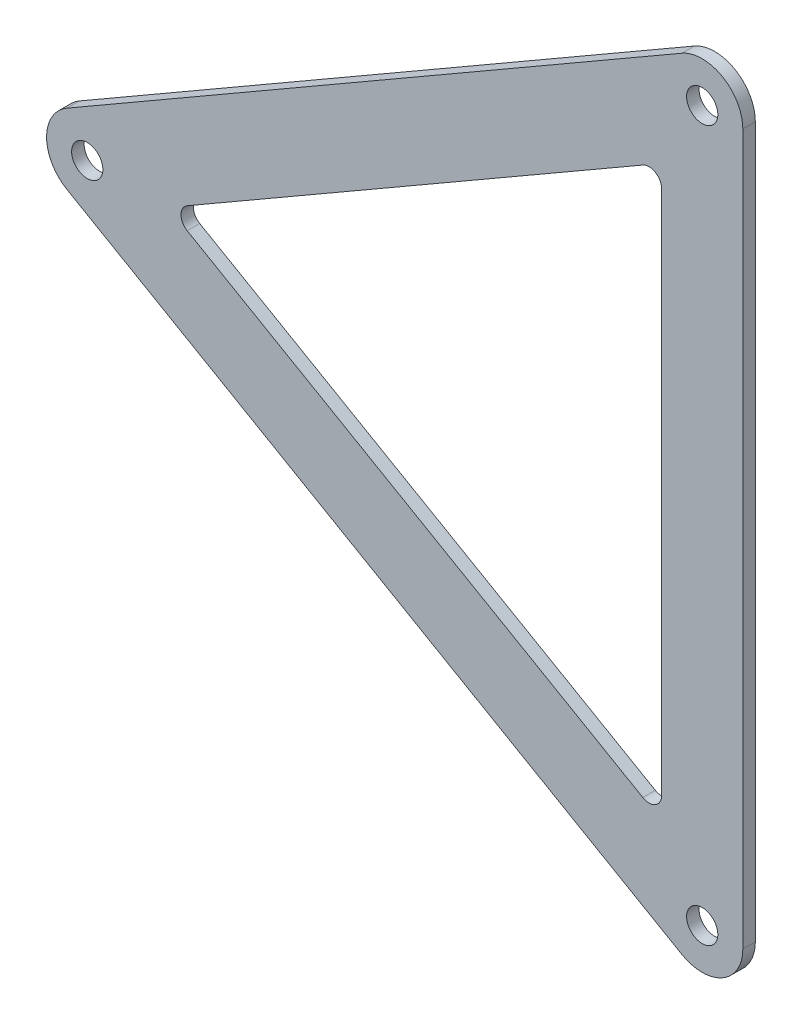
SolidWorks part; units mm, degrees
material "1060 Alloy"
ref_plane "Front Plane" through (0, 0, 0) normal (0, 0, 1) x (1, 0, 0)
ref_plane "Top Plane" through (0, 0, 0) normal (0, 1, 0) x (1, 0, 0)
ref_plane "Right Plane" through (0, 0, 0) normal (1, 0, 0) x (0, 0, -1)
sketch "Sketch1" plane through (0, 0, 0) normal (0, 0, 1) x (1, 0, 0)
  line L0 (248.5, 0) -> (353.0314, 60.3512) construction
  line L1 (248.5, 0) -> (351.6554, -59.5568) construction
  line L2 (248.5, 0) -> (359.7731, 0) construction
  line L3 (245.25, -5.6292) -> (343.6304, -62.4291)
  line L4 (245.25, 5.6292) -> (343.6304, 62.4291)
  line L5 (353.3804, -56.8) -> (353.3804, 56.8)
  line L6 (264.5, 1.7321) -> (337.3804, 43.8096)
  line L7 (254.9721, 3.7689) -> (255, 3.7528)
  line L8 (264.5, -1.7321) -> (337.3804, -43.8096)
  line L9 (340.3804, -42.0775) -> (340.3804, 42.0775)
  line L10 (251.75, 5.6292) -> (344.1046, -47.6918) construction
  line L13 (257.7758, -2.1501) -> (344.1046, 47.6918) construction
  circle A0 centre (0, 0) radius 345 construction
  circle A1 centre (0, 0) radius 255 construction
  circle A3 centre (248.5, 0) radius 2.5
  circle A4 centre (346.8804, 56.8) radius 6.5 construction
  circle A5 centre (248.5, 0) radius 6.5 construction
  circle A6 centre (346.8804, -56.8) radius 6.5 construction
  circle A7 centre (346.8804, -56.8) radius 2.5
  circle A8 centre (346.8804, 56.8) radius 2.5
  arc A9 (245.25, 5.6292) -> (245.25, -5.6292) centre (248.5, 0) ccw
  arc A10 (343.6304, -62.4291) -> (353.3804, -56.8) centre (346.8804, -56.8) ccw
  arc A11 (343.6304, 62.4291) -> (353.3804, 56.8) centre (346.8804, 56.8) cw
  arc A12 (340.3804, -42.0775) -> (337.3804, -43.8096) centre (338.3804, -42.0775) cw
  arc A13 (340.3804, 42.0775) -> (337.3804, 43.8096) centre (338.3804, 42.0775) ccw
  arc A14 (264.5, -1.7321) -> (264.5, 1.7321) centre (265.5, 0) cw
  arc A15 (344.1046, -47.6918) -> (344.1046, -47.6918) centre (344.1046, -47.6918) ccw construction
  arc A16 (344.1046, 47.6918) -> (344.1046, 47.6918) centre (344.1046, 47.6918) ccw construction
  arc A17 (257.7758, -2.1501) -> (257.7758, -2.1501) centre (257.7758, -2.1501) cw construction
  point P35 (340.3804, -56.8)
  point P36 (340.3804, 56.8)
  point P45 (261.5, 0)
  dimension "D1" = 690
  dimension "D2" = 510
  dimension "D3" = 13
  dimension "D6" = 13
  dimension "D7" = 13
  dimension "D8" = 13
  dimension "D10" = 2
  dimension "D4" = 30
  dimension "D5" = 30
  dimension "D9" = 13
extrude "Boss-Extrude1" add sketch "Sketch1" along normal blind 2
